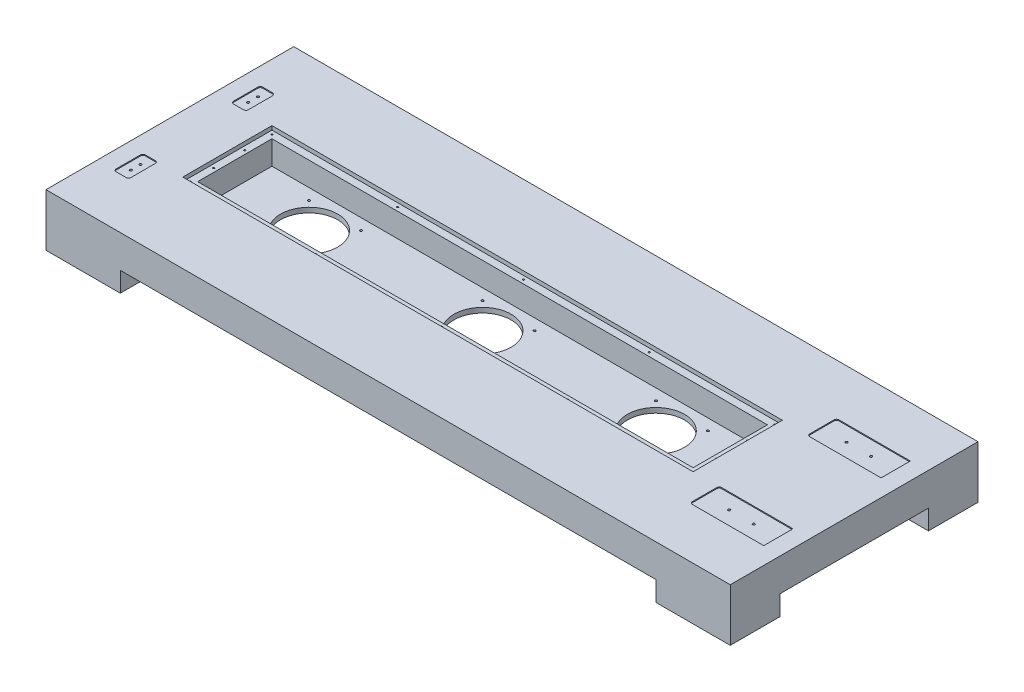
SolidWorks part; units mm, degrees
ref_plane "Front Plane" through (0, 0, 0) normal (0, 0, 1) x (1, 0, 0)
ref_plane "Top Plane" through (0, 0, 0) normal (0, 1, 0) x (1, 0, 0)
ref_plane "Right Plane" through (0, 0, 0) normal (1, 0, 0) x (0, 0, -1)
sketch "Sketch1" plane through (0, 0, 0) normal (0, 1, 0) x (1, 0, 0)
  line L1 (-750, 250) -> (750, 250)
  line L2 (-750, 250) -> (-750, -250)
  line L3 (-750, -250) -> (750, -250)
  line L4 (750, 250) -> (750, -250)
  line L5 (-750, 250) -> (750, -250) construction
  line L6 (-750, -250) -> (750, 250) construction
  point P0 (0, 0)
  dimension "D1" = 1500
  dimension "D2" = 500
sketch "Sketch19" plane through (0, 0, 0) normal (0, 1, 0) x (1, 0, 0)
  line L2 (-515, 90) -> (-515, -90)
  line L4 (-500, 75) -> (-500, -75)
  line L6 (-500, -75) -> (500, -75)
  line L8 (-515, -90) -> (515, -90)
  line L10 (-515, 90) -> (515, 90)
  line L12 (-500, 75) -> (500, 75)
  line L14 (0, 90) -> (0, -90) construction
  line L16 (500, 75) -> (500, -75)
  line L18 (515, 90) -> (515, -90)
  point P3 (-500, 0)
  dimension "D1" = 15
  dimension "D2" = 15
  dimension "D3" = 15
  dimension "D4" = 15
  dimension "D5" = 1000
  dimension "D6" = 150
extrude "Boss-Extrude2" add sketch "Sketch19" along normal blind 48 separate body
sketch "Sketch22" plane through (0, 0, 0) normal (0, 1, 0) x (1, 0, 0)
  line L1 (-515, 90) -> (515, 90)
  line L2 (-515, 90) -> (-515, -90)
  line L3 (-515, -90) -> (515, -90)
  line L4 (515, 90) -> (515, -90)
  line L5 (-515, 90) -> (515, -90) construction
  line L6 (-515, -90) -> (515, 90) construction
extrude "Boss-Extrude3" add sketch "Sketch22" against normal blind 10
sketch "Sketch23" plane through (0, 0, 0) normal (0, 1, 0) x (1, 0, 0)
  line L0 (-515, -90) -> (515, -90) construction
  line L1 (-750, 250) -> (750, 250)
  line L2 (-750, 250) -> (-750, -250)
  line L3 (-750, -250) -> (750, -250)
  line L4 (750, 250) -> (750, -250)
  line L5 (-515, 90) -> (-515, -90) construction
  line L6 (515, 90) -> (-515, 90) construction
  line L7 (515, -90) -> (515, 90) construction
  line L8 (-515, -90) -> (515, -90)
  line L9 (-515, 90) -> (-515, -90)
  line L10 (515, 90) -> (-515, 90)
  line L11 (515, -90) -> (515, 90)
extrude "Boss-Extrude4" add sketch "Sketch23" along normal offset from surface 8 and the other way up to surface (10 mm away) up to face at (0, 48, 0) offset beyond the face yes other way up to face at (0, -10, 0)
sketch "Sketch25" plane through (0, 0, 0) normal (0, -1, 0) x (1, 0, 0)
  line L0 (376.7104, 95) -> (506.8132, 123.2951) construction
  line L1 (376.7104, 133.9838) -> (510.7651, 84.6333) construction
  line L6 (-515, 90) -> (515, 90) construction
  line L8 (521.7058, 80.9826) -> (521.6427, 137.9826)
  line L9 (376.7104, 90) -> (520.9741, 90)
  line L10 (371.7104, 133.9838) -> (371.7104, 95)
  line L11 (520.6818, 138.8932) -> (376.6818, 138.9837)
  arc A0 (371.7104, 95) -> (376.7104, 90) centre (376.7104, 95) ccw
  arc A8 (520.9741, 90) -> (521.7058, 80.9826) centre (510.7651, 84.6333) ccw
  arc A10 (376.6818, 138.9837) -> (371.7104, 133.9838) centre (376.7104, 133.9838) ccw
  arc A11 (521.6427, 137.9826) -> (520.6818, 138.8932) centre (506.8132, 123.2951) ccw
  point P2 (443.2788, 109.4775)
  dimension "D5" = 5
  dimension "D2" = 5
  dimension "D1" = 144
  dimension "D4" = 57
sketch "Sketch26" plane through (0, 0, 0) normal (0, 1, 0) x (1, 0, 0)
  line L0 (-500, -75) -> (-515, -90) construction
  line L1 (-515, 90) -> (-500, 75) construction
  line L2 (500, -75) -> (515, -90) construction
  line L5 (500, 75) -> (515, 90) construction
  circle A2 centre (-507.5, -82.5) radius 1.65
  circle A3 centre (-507.5, 82.5) radius 1.65
  point P4 (-507.5, -82.5)
  point P15 (507.5, -82.5)
  point P16 (507.5, 82.5)
  dimension "D1" = 3.3
  dimension "D3" = 3.3
extrude "Cut-Extrude6" cut sketch "Sketch26" against normal blind 20 from surface at 48 starting at face at (0, 48, 0)
pattern_linear "LPattern1" count 5 spacing 253.75 along (1, 0, 0) of "Cut-Extrude6"
sketch "Sketch27" plane through (0, 0, 0) normal (0, 1, 0) x (1, 0, 0)
  line L0 (-500, 0) -> (-515, 0) construction
  line L1 (-500, 75) -> (-500, -75) construction
  line L2 (-515, -90) -> (-515, 90) construction
  line L3 (0, -36.3) -> (0, 36.3) construction
  line L6 (-507.5, 90) -> (-507.5, -90) construction
  line L7 (-515, 90) -> (515, 90) construction
  line L8 (-515, -90) -> (515, -90) construction
  line L9 (-504.8814, 84.3322) -> (-507.5, 84.15) construction
  line L10 (-507.5, 84.15) -> (-507.5, 90) construction
  line L11 (507.5, 84.15) -> (507.5, 90) construction
  line L12 (504.8814, 84.3322) -> (507.5, 84.15) construction
  line L13 (507.5, 90) -> (507.5, -90) construction
  line L14 (500, 0) -> (515, 0) construction
  circle A2 centre (-507.5, 27.5) radius 1.65
  circle A3 centre (-507.5, -35) radius 1.65
  circle A4 centre (-507.5, 82.5) radius 1.65 construction
  circle A5 centre (-507.5, 82.5) radius 1.65 construction
  circle A6 centre (507.5, -35) radius 1.65
  circle A7 centre (507.5, 27.5) radius 1.65
  point P15 (-507.9987, 90)
  dimension "D5" = 3.3
  dimension "D6" = 3.3
  dimension "D3" = 62.5
  dimension "D4" = 62.5
sketch "Sketch28" plane through (0, 0, 0) normal (0, 1, 0) x (1, 0, 0)
  line L0 (0, 0) -> (57.7, 0) construction
  line L1 (-52.5, 52.5) -> (52.5, 52.5) construction
  line L2 (-52.5, 52.5) -> (-52.5, -52.5) construction
  line L3 (-52.5, -52.5) -> (52.5, -52.5) construction
  line L4 (52.5, 52.5) -> (52.5, -52.5) construction
  line L5 (-52.5, 52.5) -> (52.5, -52.5) construction
  line L6 (-52.5, -52.5) -> (52.5, 52.5) construction
  circle A0 centre (-52.5, 52.5) radius 2.3
  circle A1 centre (52.5, 52.5) radius 2.3
  circle A2 centre (52.5, -52.5) radius 2.3
  circle A3 centre (-52.5, -52.5) radius 2.3
  circle A4 centre (0, 0) radius 57.7
  point P2 (0, 0)
  dimension "D3" = 4.6
  dimension "D4" = 4.6
  dimension "D5" = 4.6
  dimension "D6" = 4.6
  dimension "D7" = 57.7
  dimension "D1" = 105
  dimension "D2" = 105
extrude "Cut-Extrude7" cut sketch "Sketch28" against normal through all both and the other way through all
pattern_linear "LPattern2" count 2 spacing 350 along (-1, 0, 0) count 2 spacing 350 along (1, 0, 0) of "Cut-Extrude7"
extrude "Cut-Extrude8" cut sketch "Sketch27" against normal blind 20 from surface at 48 starting at face at (253.75, 48, -84.15)
sketch "Sketch30" plane through (0, 0, 0) normal (0, -1, 0) x (1, 0, 0)
  line L0 (566.5, -147.92) -> (715.5, -88.92) construction
  line L1 (566.5, -88.92) -> (715.5, -147.92) construction
  line L2 (566.5, -93.92) -> (566.5, -88.92) construction
  line L3 (566.5, -88.92) -> (571.5, -88.92) construction
  line L4 (571.5, -147.92) -> (566.5, -147.92) construction
  line L5 (566.5, -147.92) -> (566.5, -142.92) construction
  line L6 (571.5, -147.92) -> (714.5, -147.92)
  line L7 (0, 0) -> (750, 0) construction
  line L8 (715.5, -146.92) -> (715.5, -89.92)
  line L10 (566.5, -93.92) -> (566.5, -142.92)
  line L11 (714.5, -88.92) -> (571.5, -88.92)
  line L12 (750, -250) -> (750, 250) construction
  line L14 (0, 0) -> (0, -118.42) construction
  line L15 (566.5, -118.42) -> (0, -118.42) construction
  arc A0 (715.5, -89.92) -> (714.5, -88.92) centre (714.5, -89.92) ccw
  arc A1 (714.5, -147.92) -> (715.5, -146.92) centre (714.5, -146.92) ccw
  arc A9 (566.5, -142.92) -> (571.5, -147.92) centre (571.5, -142.92) ccw
  arc A10 (571.5, -88.92) -> (566.5, -93.92) centre (571.5, -93.92) ccw
  dimension "D1" = 5
  dimension "D2" = 5
  dimension "D5" = 88.92
  dimension "D6" = 566.5
  dimension "D3" = 1
  dimension "D4" = 49
  dimension "D8" = 144
extrude "Cut-Extrude9" cut sketch "Sketch30" along normal blind 2 from surface at -56 starting at face at (0, 56, 0)
mirror "Mirror1" about plane through (0, 0, 0) normal (0, 0, 1) of "Cut-Extrude9"
sketch "Sketch32" plane through (0, 0, 0) normal (0, 1, 0) x (1, 0, 0)
  line L4 (-566.5, 118.42) -> (566.5, 118.42) construction
  line L5 (-591.5, 147.92) -> (-571.5, 147.92)
  line L6 (-596.5, 142.92) -> (-596.5, 93.92)
  line L7 (-591.5, 88.92) -> (-571.5, 88.92)
  line L8 (-566.5, 142.92) -> (-566.5, 93.92)
  line L9 (566.5, 93.92) -> (566.5, 142.92) construction
  arc A4 (-566.5, 142.92) -> (-571.5, 147.92) centre (-571.5, 142.92) ccw
  arc A5 (-566.5, 93.92) -> (-571.5, 88.92) centre (-571.5, 93.92) cw
  arc A6 (-596.5, 93.92) -> (-591.5, 88.92) centre (-591.5, 93.92) ccw
  arc A7 (-596.5, 142.92) -> (-591.5, 147.92) centre (-591.5, 142.92) cw
  point P6 (-566.5, 147.92)
  point P11 (-596.5, 88.92)
  point P14 (-596.5, 147.92)
  dimension "D2" = 20
  dimension "D3" = 5
  dimension "D1" = 49
  dimension "D4" = 1133
extrude "Cut-Extrude10" cut sketch "Sketch32" against normal blind 2 from surface at 56 starting at face at (0, 56, 0)
mirror "Mirror2" about plane through (0, 0, 0) normal (0, 0, 1) of "Cut-Extrude10"
sketch "Sketch33" plane through (0, 0, 0) normal (0, 1, 0) x (1, 0, 0)
  line L0 (-581.5, 147.92) -> (-581.5, 88.92) construction
  line L1 (-571.5, 147.92) -> (-591.5, 147.92) construction
  line L2 (-591.5, 88.92) -> (-571.5, 88.92) construction
  line L3 (-581.5, -88.92) -> (-581.5, -147.92) construction
  line L4 (-591.5, -88.92) -> (-571.5, -88.92) construction
  line L5 (-571.5, -147.92) -> (-591.5, -147.92) construction
  line L6 (566.5, 118.42) -> (715.5, 118.42) construction
  line L7 (566.5, 93.92) -> (566.5, 142.92) construction
  line L8 (715.5, 146.92) -> (715.5, 89.92) construction
  line L9 (566.5, -118.42) -> (715.5, -118.42) construction
  line L10 (566.5, -93.92) -> (566.5, -142.92) construction
  line L11 (715.5, -146.92) -> (715.5, -89.92) construction
  circle A0 centre (-581.5, 108.58) radius 2.35
  circle A1 centre (-581.5, -108.59) radius 2.35
  circle A2 centre (-581.5, 128.25) radius 2.35
  circle A3 centre (-581.5, -128.26) radius 2.35
  circle A4 centre (616.17, -118.42) radius 2.35
  circle A5 centre (665.84, -118.42) radius 2.35
  circle A6 centre (616.17, 118.42) radius 2.35
  circle A7 centre (665.84, 118.42) radius 2.35
  dimension "D1" = 4.7
  dimension "D2" = 4.7
  dimension "D3" = 4.7
  dimension "D8" = 4.7
  dimension "D11" = 4.7
  dimension "D12" = 4.7
  dimension "D13" = 4.7
  dimension "D14" = 4.7
  dimension "D4" = 19.67
  dimension "D5" = 19.67
  dimension "D6" = 19.67
  dimension "D7" = 19.67
  dimension "D9" = 49.67
  dimension "D10" = 49.67
extrude "Cut-Extrude11" cut sketch "Sketch33" against normal through all both and the other way through all
sketch "Sketch34" plane through (0, 0, 0) normal (0, 1, 0) x (1, 0, 0)
  line L0 (-596.5, -118.42) -> (-631, -118.42) construction
  line L1 (-596.5, -142.92) -> (-596.5, -93.92) construction
  line L2 (750, -250) -> (-750, -250) construction
  line L3 (-631, -250) -> (-821.8308, -250)
  line L4 (-631, -250) -> (-631, 290.53)
  line L5 (-631, 290.53) -> (-821.8308, 290.53)
  line L6 (-821.8308, -250) -> (-821.8308, 290.53)
  dimension "D1" = 34.5
extrude "Cut-Extrude12" cut sketch "Sketch34" along normal through all both and the other way through all
sketch "Sketch29" plane through (0, 0, 0) normal (0, 1, 0) x (1, 0, 0)
  line L1 (-631, -250) -> (-481, -250)
  line L2 (-631, -250) -> (-631, -150)
  line L3 (-631, -150) -> (-481, -150)
  line L4 (-481, -250) -> (-481, -150)
  line L5 (-631, 250) -> (-481, 250)
  line L6 (-631, 250) -> (-631, 150)
  line L7 (-631, 150) -> (-481, 150)
  line L8 (-481, 250) -> (-481, 150)
  line L9 (750, -250) -> (600, -250)
  line L10 (750, -250) -> (750, -150)
  line L11 (750, -150) -> (600, -150)
  line L12 (600, -250) -> (600, -150)
  line L13 (750, 250) -> (600, 250)
  line L14 (750, 250) -> (750, 150)
  line L15 (750, 150) -> (600, 150)
  line L16 (600, 250) -> (600, 150)
  dimension "D1" = 150
  dimension "D2" = 100
  dimension "D3" = 150
  dimension "D4" = 100
  dimension "D5" = 150
  dimension "D6" = 100
  dimension "D7" = 100
  dimension "D8" = 150
extrude "Boss-Extrude5" add sketch "Sketch29" against normal blind 50
